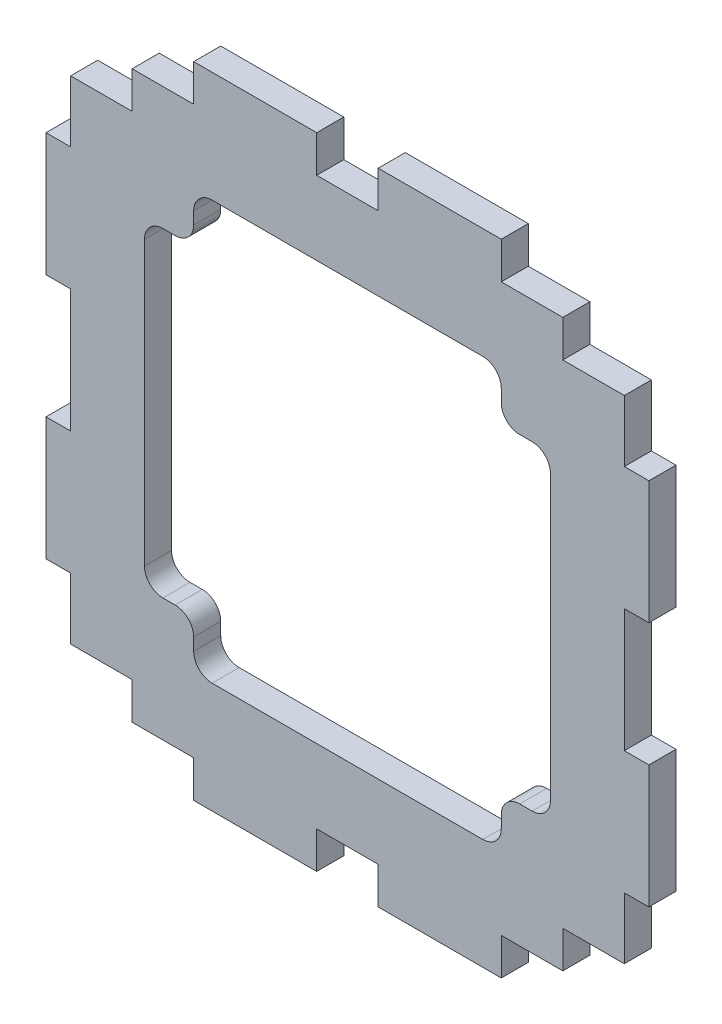
SolidWorks part; units mm, degrees
ref_plane "前视基准面" through (0, 0, 0) normal (0, 0, 1) x (1, 0, 0)
ref_plane "上视基准面" through (0, 0, 0) normal (0, 1, 0) x (1, 0, 0)
ref_plane "右视基准面" through (0, 0, 0) normal (1, 0, 0) x (0, 0, -1)
sketch "Model" plane through (0, 0, 0) normal (0, 0, 1) x (1, 0, 0)
  line L0 (16.0925, 13.8089) -> (15.0925, 13.8089)
  line L1 (13.5925, 15.3089) -> (13.5925, 16.3089)
  line L2 (12.0925, 17.8089) -> (-9.9075, 17.8089)
  line L3 (-11.4075, 16.3089) -> (-11.4075, 15.3089)
  line L4 (-12.9075, 13.8089) -> (-13.9075, 13.8089)
  line L5 (-15.4075, 12.3089) -> (-15.4075, -10.6911)
  line L6 (-13.9075, -12.1911) -> (-12.9075, -12.1911)
  line L7 (-11.4075, -13.6911) -> (-11.4075, -14.6911)
  line L8 (-9.9075, -16.1911) -> (12.0925, -16.1911)
  line L9 (13.5925, -14.6911) -> (13.5925, -13.6911)
  line L10 (15.0925, -12.1911) -> (16.0925, -12.1911)
  line L11 (17.5925, -10.6911) -> (17.5925, 12.3089)
  line L12 (-11.4075, -25.1911) -> (-11.4075, -22.1911)
  line L13 (-11.4075, -22.1911) -> (-16.4075, -22.1911)
  line L14 (-16.4075, -22.1911) -> (-16.4075, -19.1911)
  line L15 (-16.4075, -19.1911) -> (-21.4075, -19.1911)
  line L16 (-21.4075, -19.1911) -> (-21.4075, -14.1911)
  line L17 (-21.4075, -14.1911) -> (-23.4075, -14.1911)
  line L18 (-23.4075, -14.1911) -> (-23.4075, -4.1911)
  line L19 (-23.4075, -4.1911) -> (-21.4075, -4.1911)
  line L20 (-21.4075, -4.1911) -> (-21.4075, 5.8089)
  line L21 (-21.4075, 5.8089) -> (-23.4075, 5.8089)
  line L22 (-23.4075, 5.8089) -> (-23.4075, 15.8089)
  line L23 (-23.4075, 15.8089) -> (-21.4075, 15.8089)
  line L24 (-21.4075, 15.8089) -> (-21.4075, 20.8089)
  line L25 (-21.4075, 20.8089) -> (-16.4075, 20.8089)
  line L26 (-16.4075, 20.8089) -> (-16.4075, 23.8089)
  line L27 (-16.4075, 23.8089) -> (-11.4075, 23.8089)
  line L28 (-11.4075, 23.8089) -> (-11.4075, 26.8089)
  line L29 (-11.4075, 26.8089) -> (-1.4075, 26.8089)
  line L30 (-1.4075, 26.8089) -> (-1.4075, 23.8089)
  line L31 (-1.4075, 23.8089) -> (3.5925, 23.8089)
  line L32 (3.5925, 23.8089) -> (3.5925, 26.8089)
  line L33 (3.5925, 26.8089) -> (13.5925, 26.8089)
  line L34 (13.5925, 26.8089) -> (13.5925, 23.8089)
  line L35 (13.5925, 23.8089) -> (18.5925, 23.8089)
  line L36 (18.5925, 23.8089) -> (18.5925, 20.8089)
  line L37 (18.5925, 20.8089) -> (23.5925, 20.8089)
  line L38 (23.5925, 20.8089) -> (23.5925, 15.8089)
  line L39 (23.5925, 15.8089) -> (25.5925, 15.8089)
  line L40 (25.5925, 15.8089) -> (25.5925, 5.8089)
  line L41 (25.5925, 5.8089) -> (23.5925, 5.8089)
  line L42 (23.5925, 5.8089) -> (23.5925, -4.1911)
  line L43 (23.5925, -4.1911) -> (25.5925, -4.1911)
  line L44 (25.5925, -4.1911) -> (25.5925, -14.1911)
  line L45 (25.5925, -14.1911) -> (23.5925, -14.1911)
  line L46 (23.5925, -14.1911) -> (23.5925, -19.1911)
  line L47 (23.5925, -19.1911) -> (18.5925, -19.1911)
  line L48 (18.5925, -19.1911) -> (18.5925, -22.1911)
  line L49 (18.5925, -22.1911) -> (13.5925, -22.1911)
  line L50 (13.5925, -22.1911) -> (13.5925, -25.1911)
  line L51 (13.5925, -25.1911) -> (3.5925, -25.1911)
  line L52 (3.5925, -25.1911) -> (3.5925, -22.1911)
  line L53 (3.5925, -22.1911) -> (-1.4075, -22.1911)
  line L54 (-1.4075, -22.1911) -> (-1.4075, -25.1911)
  line L55 (-1.4075, -25.1911) -> (-11.4075, -25.1911)
  arc A0 (17.5925, 12.3089) -> (16.0925, 13.8089) centre (16.0925, 12.3089) ccw
  arc A1 (13.5925, 15.3089) -> (15.0925, 13.8089) centre (15.0925, 15.3089) ccw
  arc A2 (13.5925, 16.3089) -> (12.0925, 17.8089) centre (12.0925, 16.3089) ccw
  arc A3 (-9.9075, 17.8089) -> (-11.4075, 16.3089) centre (-9.9075, 16.3089) ccw
  arc A4 (-12.9075, 13.8089) -> (-11.4075, 15.3089) centre (-12.9075, 15.3089) ccw
  arc A5 (-13.9075, 13.8089) -> (-15.4075, 12.3089) centre (-13.9075, 12.3089) ccw
  arc A6 (-15.4075, -10.6911) -> (-13.9075, -12.1911) centre (-13.9075, -10.6911) ccw
  arc A7 (-11.4075, -13.6911) -> (-12.9075, -12.1911) centre (-12.9075, -13.6911) ccw
  arc A8 (-11.4075, -14.6911) -> (-9.9075, -16.1911) centre (-9.9075, -14.6911) ccw
  arc A9 (12.0925, -16.1911) -> (13.5925, -14.6911) centre (12.0925, -14.6911) ccw
  arc A10 (15.0925, -12.1911) -> (13.5925, -13.6911) centre (15.0925, -13.6911) ccw
  arc A11 (16.0925, -12.1911) -> (17.5925, -10.6911) centre (16.0925, -10.6911) ccw
extrude "凸台-拉伸1" add sketch "Model" along normal blind 2.2
